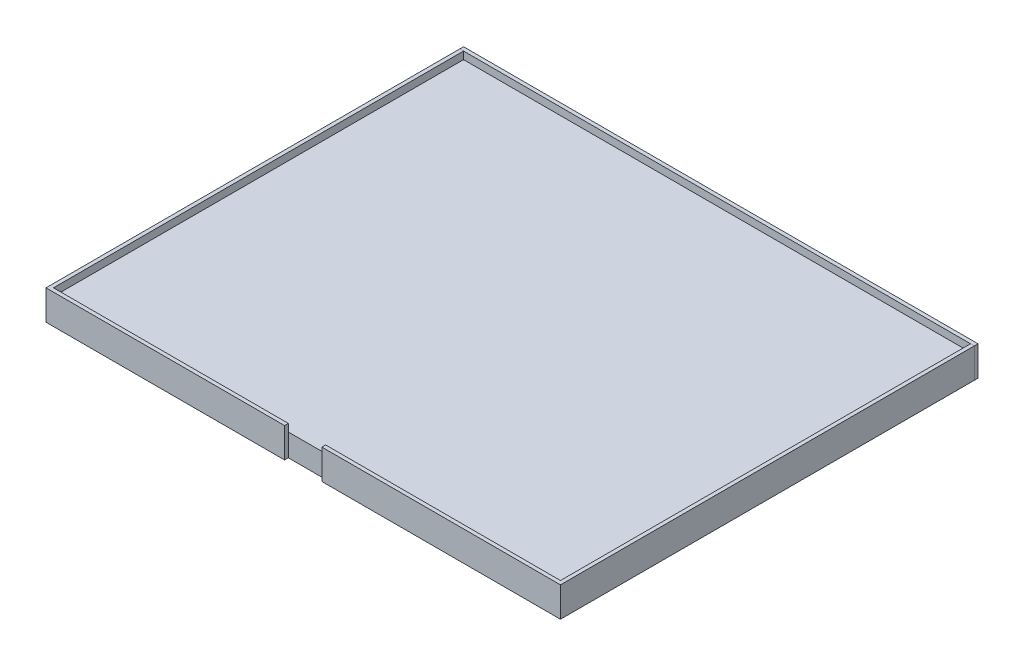
SolidWorks part; units mm, degrees
ref_plane "Front" through (0, 0, 0) normal (0, 0, 1) x (1, 0, 0)
ref_plane "Top" through (0, 0, 0) normal (0, 1, 0) x (1, 0, 0)
ref_plane "Right" through (0, 0, 0) normal (1, 0, 0) x (0, 0, -1)
sketch "Sketch1" plane through (0, 0, 0) normal (0, 1, 0) x (1, 0, 0)
  line L1 (0, 0) -> (431.8, 0)
  line L2 (0, 0) -> (0, 349.25)
  line L3 (0, 349.25) -> (431.8, 349.25)
  line L4 (431.8, 0) -> (431.8, 349.25)
  line L5 (0, 0) -> (431.8, 349.25) construction
  line L6 (0, 349.25) -> (431.8, 0) construction
  point P4 (215.9, 174.625)
  dimension "D1" = 349.25
  dimension "D2" = 431.8
extrude "Boss-Extrude1" add sketch "Sketch1" along normal blind 19.05
sketch "Sketch2" plane through (0, 0, 0) normal (0, -1, 0) x (1, 0, 0)
  line L0 (0, -349.25) -> (0, 0) construction
  line L1 (431.8, 0) -> (431.8, -349.25) construction
  line L2 (0, 0) -> (431.8, 0) construction
  line L3 (0, -349.25) -> (0, 0)
  line L4 (431.8, 0) -> (431.8, -349.25)
  line L5 (0, 0) -> (431.8, 0)
  line L6 (-3.175, -349.25) -> (-3.175, 3.175)
  line L7 (-3.175, 3.175) -> (434.975, 3.175)
  line L8 (434.975, 3.175) -> (434.975, -349.25)
  line L9 (0, -349.25) -> (-3.175, -349.25)
  line L10 (431.8, -349.25) -> (434.975, -349.25)
  dimension "D1" = 3.175
extrude "Boss-Extrude2" add sketch "Sketch2" against normal blind 25.4 separate body
sketch "Sketch3" plane through (0, 0, 3.175) normal (0, 0, 1) x (1, 0, 0)
  line L0 (215.9, 25.4) -> (215.9, 0) construction
  line L1 (434.975, 25.4) -> (-3.175, 25.4) construction
  line L2 (434.975, 0) -> (-3.175, 0) construction
  line L4 (200.025, 0) -> (231.775, 0)
  line L5 (200.025, 0) -> (200.025, 25.4)
  line L6 (200.025, 25.4) -> (231.775, 25.4)
  line L7 (231.775, 0) -> (231.775, 25.4)
  line L8 (200.025, 0) -> (231.775, 25.4) construction
  line L9 (200.025, 25.4) -> (231.775, 0) construction
  point P6 (215.9, 12.7)
  dimension "D1" = 31.75
extrude "Cut-Extrude2" cut sketch "Sketch3" against normal blind 3.175
sketch "Sketch4" plane through (0, 0, -349.25) normal (0, 0, -1) x (-1, 0, 0)
  line L0 (3.175, 25.4) -> (3.175, 0) construction
  line L1 (-434.975, 25.4) -> (3.175, 25.4)
  line L2 (-434.975, 25.4) -> (-434.975, 0)
  line L3 (-434.975, 0) -> (3.175, 0)
  line L4 (3.175, 25.4) -> (3.175, 0)
  line L5 (-434.975, 25.4) -> (3.175, 0) construction
  line L6 (-434.975, 0) -> (3.175, 25.4) construction
  point P4 (-215.9, 12.7)
extrude "Boss-Extrude3" add sketch "Sketch4" along normal blind 3.175 separate body
